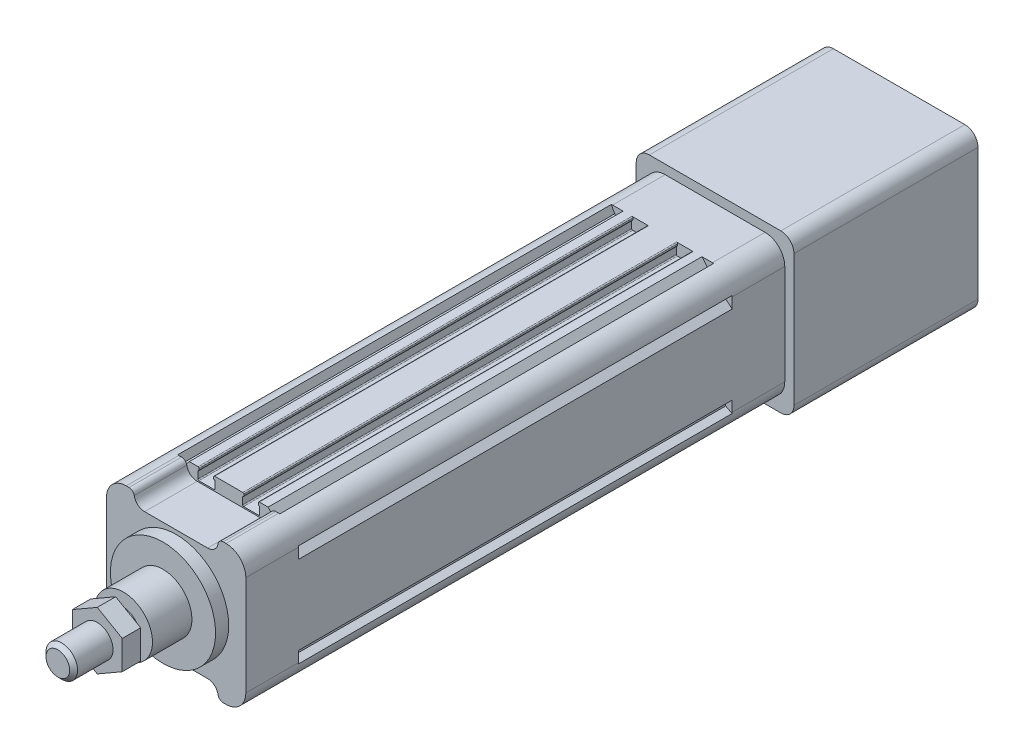
SolidWorks part; units mm, degrees
ref_plane "Front" through (0, 0, 0) normal (0, 0, 1) x (1, 0, 0)
ref_plane "Top" through (0, 0, 0) normal (0, 1, 0) x (1, 0, 0)
ref_plane "Right" through (0, 0, 0) normal (1, 0, 0) x (0, 0, -1)
sketch "草图1" plane through (0, 0, 0) normal (0, 0, 1) x (1, 0, 0)
  line L0 (19.7737, 3) -> (23.3, 3)
  line L1 (23.3, 3) -> (23.3, -3)
  line L2 (23.3, -3) -> (19.7737, -3)
  line L3 (-19.7737, -3) -> (-23.3, -3)
  line L4 (-23.3, -3) -> (-23.3, 3)
  line L5 (-23.3, 3) -> (-19.7737, 3)
  line L6 (-18.2, 24) -> (-19.4434, 26.4869)
  line L7 (-26.4869, 19.4434) -> (-24, 18.2)
  line L8 (-24, 18.2) -> (-24, 17.1)
  line L9 (-24, 17.1) -> (-26.5, 15)
  line L10 (-26.5, 15) -> (-26.5, -15)
  line L11 (-26.5, -15) -> (-24, -17.1)
  line L12 (-24, -17.1) -> (-24, -18.2)
  line L13 (-24, -18.2) -> (-26.4869, -19.4434)
  line L14 (-19.4434, -26.4869) -> (-18.2, -24)
  line L15 (-18.2, -24) -> (-17.1, -24)
  line L16 (-17.1, -24) -> (-15, -26.5)
  line L17 (-15, -26.5) -> (-11.65, -26.5)
  line L18 (-11.25, -26.1) -> (-11.25, -25.6)
  line L19 (-11.65, -25.2) -> (-11.75, -25.2)
  line L20 (-11.75, -25.2) -> (-11.75, -22.4)
  line L21 (-11.35, -22) -> (-5.65, -22)
  line L22 (-5.25, -22.4) -> (-5.25, -25.2)
  line L23 (-5.25, -25.2) -> (-5.35, -25.2)
  line L24 (-5.75, -25.6) -> (-5.75, -26.1)
  line L25 (-5.35, -26.5) -> (5.35, -26.5)
  line L26 (5.75, -26.1) -> (5.75, -25.6)
  line L27 (5.35, -25.2) -> (5.25, -25.2)
  line L28 (5.25, -25.2) -> (5.25, -22.4)
  line L29 (5.65, -22) -> (11.35, -22)
  line L30 (11.75, -22.4) -> (11.75, -25.2)
  line L31 (11.75, -25.2) -> (11.65, -25.2)
  line L32 (11.25, -25.6) -> (11.25, -26.1)
  line L33 (11.65, -26.5) -> (15, -26.5)
  line L34 (15, -26.5) -> (17.1, -24)
  line L35 (17.1, -24) -> (18.2, -24)
  line L36 (18.2, -24) -> (19.4434, -26.4869)
  line L37 (26.4869, -19.4434) -> (24, -18.2)
  line L38 (24, -18.2) -> (24, -17.1)
  line L39 (24, -17.1) -> (26.5, -15)
  line L40 (26.5, -15) -> (26.5, 15)
  line L41 (26.5, 15) -> (24, 17.1)
  line L42 (24, 17.1) -> (24, 18.2)
  line L43 (24, 18.2) -> (26.4869, 19.4434)
  line L44 (19.4434, 26.4869) -> (18.2, 24)
  line L45 (18.2, 24) -> (17.1, 24)
  line L46 (17.1, 24) -> (15, 26.5)
  line L47 (15, 26.5) -> (11.65, 26.5)
  line L48 (11.25, 26.1) -> (11.25, 25.6)
  line L49 (11.65, 25.2) -> (11.75, 25.2)
  line L50 (11.75, 25.2) -> (11.75, 22.4)
  line L51 (11.35, 22) -> (5.65, 22)
  line L52 (5.25, 22.4) -> (5.25, 25.2)
  line L53 (5.25, 25.2) -> (5.35, 25.2)
  line L54 (5.75, 25.6) -> (5.75, 26.1)
  line L55 (5.35, 26.5) -> (-5.35, 26.5)
  line L56 (-5.75, 26.1) -> (-5.75, 25.6)
  line L57 (-5.35, 25.2) -> (-5.25, 25.2)
  line L58 (-5.25, 25.2) -> (-5.25, 22.4)
  line L59 (-5.65, 22) -> (-11.35, 22)
  line L60 (-11.75, 22.4) -> (-11.75, 25.2)
  line L61 (-11.75, 25.2) -> (-11.65, 25.2)
  line L62 (-11.25, 25.6) -> (-11.25, 26.1)
  line L63 (-11.65, 26.5) -> (-15, 26.5)
  line L64 (-15, 26.5) -> (-17.1, 24)
  line L65 (-17.1, 24) -> (-18.2, 24)
  arc A0 (19.7737, 3) -> (-19.7737, 3) centre (0, 0) ccw
  arc A1 (-19.7737, -3) -> (19.7737, -3) centre (0, 0) ccw
  circle A2 centre (19, 19) radius 2.1
  circle A3 centre (19, -19) radius 2.1
  circle A4 centre (-19, -19) radius 2.1
  circle A5 centre (-19, 19) radius 2.1
  arc A6 (-19.4434, 26.4869) -> (-26.4869, 19.4434) centre (-19, 19) ccw
  arc A7 (-26.4869, -19.4434) -> (-19.4434, -26.4869) centre (-19, -19) ccw
  arc A8 (-11.65, -26.5) -> (-11.25, -26.1) centre (-11.65, -26.1) ccw
  arc A9 (-11.25, -25.6) -> (-11.65, -25.2) centre (-11.65, -25.6) ccw
  arc A10 (-11.35, -22) -> (-11.75, -22.4) centre (-11.35, -22.4) ccw
  arc A11 (-5.25, -22.4) -> (-5.65, -22) centre (-5.65, -22.4) ccw
  arc A12 (-5.35, -25.2) -> (-5.75, -25.6) centre (-5.35, -25.6) ccw
  arc A13 (-5.75, -26.1) -> (-5.35, -26.5) centre (-5.35, -26.1) ccw
  arc A14 (5.35, -26.5) -> (5.75, -26.1) centre (5.35, -26.1) ccw
  arc A15 (5.75, -25.6) -> (5.35, -25.2) centre (5.35, -25.6) ccw
  arc A16 (5.65, -22) -> (5.25, -22.4) centre (5.65, -22.4) ccw
  arc A17 (11.75, -22.4) -> (11.35, -22) centre (11.35, -22.4) ccw
  arc A18 (11.65, -25.2) -> (11.25, -25.6) centre (11.65, -25.6) ccw
  arc A19 (11.25, -26.1) -> (11.65, -26.5) centre (11.65, -26.1) ccw
  arc A20 (19.4434, -26.4869) -> (26.4869, -19.4434) centre (19, -19) ccw
  arc A21 (26.4869, 19.4434) -> (19.4434, 26.4869) centre (19, 19) ccw
  arc A22 (11.65, 26.5) -> (11.25, 26.1) centre (11.65, 26.1) ccw
  arc A23 (11.25, 25.6) -> (11.65, 25.2) centre (11.65, 25.6) ccw
  arc A24 (11.35, 22) -> (11.75, 22.4) centre (11.35, 22.4) ccw
  arc A25 (5.25, 22.4) -> (5.65, 22) centre (5.65, 22.4) ccw
  arc A26 (5.35, 25.2) -> (5.75, 25.6) centre (5.35, 25.6) ccw
  arc A27 (5.75, 26.1) -> (5.35, 26.5) centre (5.35, 26.1) ccw
  arc A28 (-5.35, 26.5) -> (-5.75, 26.1) centre (-5.35, 26.1) ccw
  arc A29 (-5.75, 25.6) -> (-5.35, 25.2) centre (-5.35, 25.6) ccw
  arc A30 (-5.65, 22) -> (-5.25, 22.4) centre (-5.65, 22.4) ccw
  arc A31 (-11.75, 22.4) -> (-11.35, 22) centre (-11.35, 22.4) ccw
  arc A32 (-11.65, 25.2) -> (-11.25, 25.6) centre (-11.65, 25.6) ccw
  arc A33 (-11.25, 26.1) -> (-11.65, 26.5) centre (-11.65, 26.1) ccw
extrude "凸台-拉伸1" add sketch "草图1" along normal blind 165
sketch "草图6" plane through (0, 0, 165) normal (0, 0, 1) x (1, 0, 0)
  line L0 (0, 0) -> (19, 0) construction
  line L2 (-26.5, -19) -> (-26.5, 19)
  line L3 (-19, 26.5) -> (-17.9161, 26.5)
  line L4 (26.5, -19) -> (26.5, 19)
  line L5 (-26.5, -26.5) -> (26.5, 26.5) construction
  line L6 (-26.5, 26.5) -> (26.5, -26.5) construction
  line L7 (-12, 21.5) -> (12, 21.5)
  line L9 (19, 26.5) -> (17.9161, 26.5)
  line L10 (19, -26.5) -> (17.9161, -26.5)
  line L11 (-12, -21.5) -> (12, -21.5)
  line L12 (-19, -26.5) -> (-17.9161, -26.5)
  arc A0 (12, 21.5) -> (15.9441, 24.8333) centre (12, 25.5) ccw
  arc A1 (-15.9441, 24.8333) -> (-12, 21.5) centre (-12, 25.5) ccw
  arc A2 (-15.9441, 24.8333) -> (-17.9161, 26.5) centre (-17.9161, 24.5) ccw
  arc A3 (15.9441, 24.8333) -> (17.9161, 26.5) centre (17.9161, 24.5) cw
  arc A4 (-26.5, -19) -> (-19, -26.5) centre (-19, -19) ccw
  arc A5 (19, -26.5) -> (26.5, -19) centre (19, -19) ccw
  arc A6 (26.5, 19) -> (19, 26.5) centre (19, 19) ccw
  arc A7 (-26.5, 19) -> (-19, 26.5) centre (-19, 19) cw
  arc A8 (15.9441, -24.8333) -> (17.9161, -26.5) centre (17.9161, -24.5) ccw
  arc A9 (12, -21.5) -> (15.9441, -24.8333) centre (12, -25.5) cw
  arc A10 (-15.9441, -24.8333) -> (-12, -21.5) centre (-12, -25.5) cw
  arc A11 (-15.9441, -24.8333) -> (-17.9161, -26.5) centre (-17.9161, -24.5) cw
  point P0 (0, 0)
  point P9 (0, 21.5)
  point P13 (20, 20.8461)
  point P16 (-12, 20.8461)
  dimension "D5" = 4
  dimension "D6" = 2
  dimension "D7" = 2
  dimension "D9" = 7.5
  dimension "D1" = 53
  dimension "D2" = 53
  dimension "D3" = 26.5
  dimension "D4" = 24
  dimension "D8" = 5
extrude "凸台-拉伸2" add sketch "草图6" along normal blind 20
sketch "草图7" plane through (0, 0, 185) normal (0, 0, 1) x (1, 0, 0)
  circle A0 centre (0, 0) radius 20
  dimension "D1" = 40
extrude "凸台-拉伸3" add sketch "草图7" along normal blind 5
sketch "草图9" plane through (0, 0, 190) normal (0, 0, 1) x (1, 0, 0)
  circle A0 centre (0, 0) radius 11
  dimension "D1" = 22
extrude "凸台-拉伸4" add sketch "草图9" along normal blind 15
sketch "草图10" plane through (0, 0, 205) normal (0, 0, 1) x (1, 0, 0)
  circle A0 centre (0, 0) radius 6
  dimension "D1" = 12
extrude "凸台-拉伸5" add sketch "草图10" along normal blind 25
sketch "草图11" plane through (0, 0, 0) normal (0, 0, -1) x (-1, 0, 0)
  line L1 (-19, -26.5) -> (19, -26.5)
  line L2 (-26.5, -19) -> (-26.5, 19)
  line L3 (-19, 26.5) -> (19, 26.5)
  line L4 (26.5, -19) -> (26.5, 19)
  line L5 (-26.5, -26.5) -> (26.5, 26.5) construction
  line L6 (-26.5, 26.5) -> (26.5, -26.5) construction
  arc A0 (-26.5, -19) -> (-19, -26.5) centre (-19, -19) ccw
  arc A1 (19, -26.5) -> (26.5, -19) centre (19, -19) ccw
  arc A2 (26.5, 19) -> (19, 26.5) centre (19, 19) ccw
  arc A3 (-26.5, 19) -> (-19, 26.5) centre (-19, 19) cw
  point P0 (0, 0)
  dimension "D3" = 7.5
  dimension "D1" = 53
  dimension "D2" = 53
extrude "凸台-拉伸6" add sketch "草图11" along normal blind 20
sketch "草图12" plane through (0, 0, -20) normal (0, 0, -1) x (-1, 0, 0)
  line L1 (-25, -30) -> (25, -30)
  line L2 (-30, -25) -> (-30, 25)
  line L3 (-25, 30) -> (25, 30)
  line L4 (30, -25) -> (30, 25)
  line L5 (-30, -30) -> (30, 30) construction
  line L6 (-30, 30) -> (30, -30) construction
  arc A0 (-30, -25) -> (-25, -30) centre (-25, -25) ccw
  arc A1 (25, -30) -> (30, -25) centre (25, -25) ccw
  arc A2 (30, 25) -> (25, 30) centre (25, 25) ccw
  arc A3 (-30, 25) -> (-25, 30) centre (-25, 25) cw
  point P0 (0, 0)
  dimension "D3" = 5
  dimension "D1" = 60
  dimension "D2" = 60
extrude "凸台-拉伸7" add sketch "草图12" along normal blind 70
sketch "草图14" plane through (0, 0, -90) normal (0, 0, -1) x (-1, 0, 0)
  circle A0 centre (0, 0) radius 19
  dimension "D1" = 38
extrude "切除-拉伸2" cut sketch "草图14" against normal blind 70
hole_wizard "M6 螺纹孔1" positions "草图15" profile "草图16" tap size "M6" standard "GB"
sketch "草图15" plane through (-26.5, 0, 0) normal (-1, 0, 0) x (0, 0, 1)
  line L0 (-20, -25) -> (-20, 25) construction
  line L1 (185, 19) -> (185, -19) construction
  point P0 (175, 11)
  point P2 (175, -11)
  point P4 (-10, 11)
  point P6 (-10, -11)
  dimension "D1" = 10
  dimension "D2" = 10
  dimension "D3" = 11
  dimension "D4" = 11
  dimension "D5" = 10
  dimension "D6" = 10
  dimension "D7" = 22
  dimension "D8" = 11
sketch "草图16" plane through (-26.5, 11, 175) normal (0, 1, 0) x (0, 0, 1)
  line L0 (0, 0) -> (0, 16.5022)
  line L1 (0, 16.5022) -> (2.5, 15)
  line L2 (2.5, 15) -> (2.5, 0)
  line L5 (2.5, 0) -> (0, 0)
  line L10 (0, 16.5022) -> (-2.5, 15) construction
  line L11 (0, -6.35) -> (0, 107.95) construction
  dimension "螺纹孔钻头直径" = 5
  dimension "螺纹孔钻头深度" = 15
  dimension "导头角度" = 118
cosmetic thread "孔螺蚊线4" parameters "D1"=12, "D2"=6
cosmetic thread "孔螺蚊线5" parameters "D1"=12, "D2"=6
cosmetic thread "孔螺蚊线6" parameters "D1"=12, "D2"=6
cosmetic thread "孔螺蚊线7" parameters "D1"=12, "D2"=6
chamfer "倒角1" distance 1.5 angle 45 1 edges at (6, 0, 230)
sketch "草图17" plane through (0, 0, 205) normal (0, 0, 1) x (1, 0, 0)
  line L1 (0, 10.9697) -> (-9.5, 5.4848)
  line L2 (-9.5, 5.4848) -> (-9.5, -5.4848)
  line L3 (-9.5, -5.4848) -> (0, -10.9697)
  line L4 (0, -10.9697) -> (9.5, -5.4848)
  line L5 (9.5, -5.4848) -> (9.5, 5.4848)
  line L6 (9.5, 5.4848) -> (0, 10.9697)
  circle A0 centre (0, 0) radius 9.5 construction
  dimension "D1" = 19
extrude "凸台-拉伸8" add sketch "草图17" along normal blind 7 from offset 3
